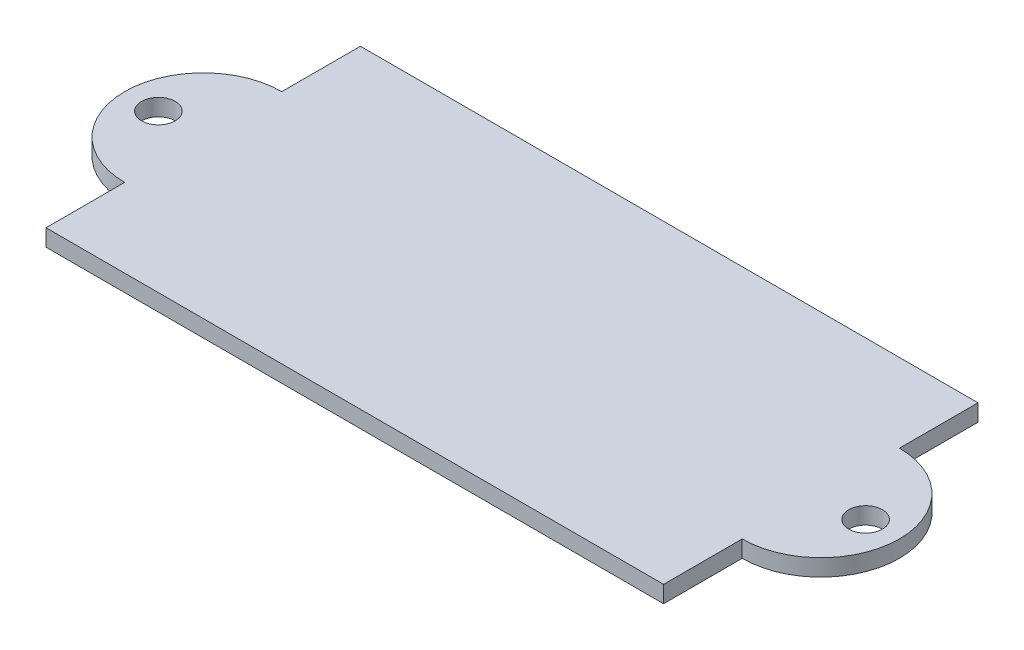
SolidWorks part; units mm, degrees
ref_plane "Front Plane" through (0, 0, 0) normal (0, 0, 1) x (1, 0, 0)
ref_plane "Top Plane" through (0, 0, 0) normal (0, 1, 0) x (1, 0, 0)
ref_plane "Right Plane" through (0, 0, 0) normal (1, 0, 0) x (0, 0, -1)
sketch "Sketch1" plane through (0, 0, 0) normal (0, 1, 0) x (1, 0, 0)
  line L0 (-27.5, 0) -> (52.5678, 0) construction
  line L1 (-27.5, 14) -> (27.5, 14)
  line L2 (-27.5, 14) -> (-27.5, -14)
  line L3 (-27.5, -14) -> (27.5, -14)
  line L4 (27.5, 14) -> (27.5, -14)
  line L5 (-27.5, 14) -> (27.5, -14) construction
  line L6 (-27.5, -14) -> (27.5, 14) construction
  line L7 (0, 0) -> (0, -59.4575) construction
  arc A0 (-27.5, 7) -> (-27.5, -7) centre (-27.5, 0) ccw
  arc A1 (27.5, 7) -> (27.5, -7) centre (27.5, 0) cw
  point P0 (0, 0)
  point P15 (31.49, 0)
  point P16 (-31.49, 0)
  dimension "D3" = 7
  dimension "D1" = 55
  dimension "D2" = 28
  dimension "D4" = 3.99
extrude "Boss-Extrude1" add sketch "Sketch1" against normal blind 1.5 contours L4 L1 L2 L3 | L2 A0 | A1 L4
sketch "Sketch4" plane through (0, 0, 0) normal (0, 1, 0) x (1, 0, 0)
  circle A0 centre (-31.49, 0) radius 1.5
  circle A1 centre (31.49, 0) radius 1.5
  dimension "D1" = 3
  dimension "D2" = 3
extrude "Cut-Extrude1" cut sketch "Sketch4" against normal through all
